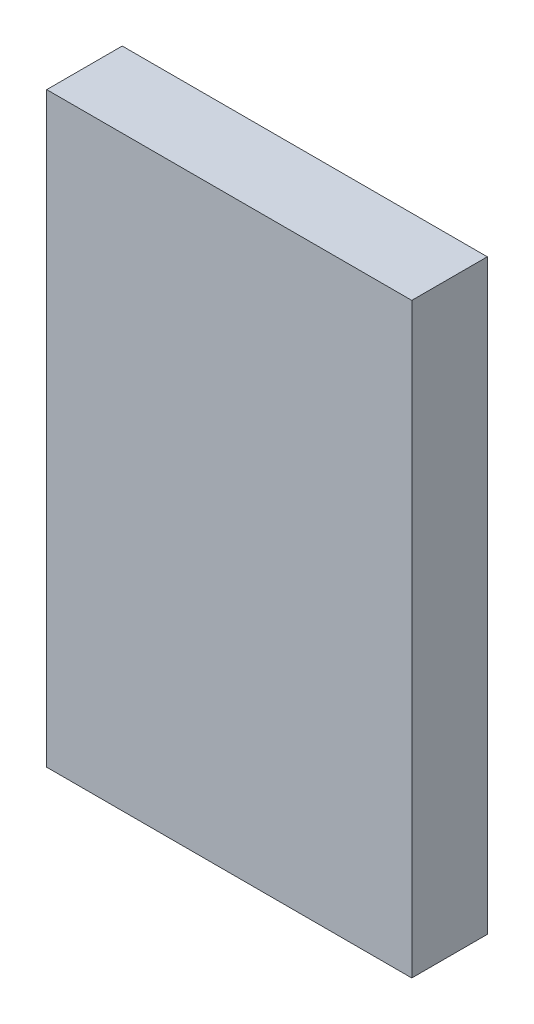
SolidWorks part; units mm, degrees
ref_plane "Front Plane" through (0, 0, 0) normal (0, 0, 1) x (1, 0, 0)
ref_plane "Top Plane" through (0, 0, 0) normal (0, 1, 0) x (1, 0, 0)
ref_plane "Right Plane" through (0, 0, 0) normal (1, 0, 0) x (0, 0, -1)
sketch "Sketch1" plane through (0, 0, 0) normal (0, 0, 1) x (1, 0, 0)
  line L0 (0.0436, 13.3694) -> (0.0436, -7.1259) construction
  line L1 (-7.2064, -7.1306) -> (-7.2064, 13.3694)
  line L2 (-7.2064, 13.3694) -> (7.2936, 13.3694)
  line L3 (7.2936, -6.9397) -> (7.2936, 13.3694)
  line L4 (-7.2064, -7.1306) -> (7.2936, 13.3694) construction
  line L5 (-7.2064, 13.3694) -> (7.2936, -6.9397) construction
  line L6 (-4.4564, -7.1306) -> (-4.4564, -4.1306)
  line L7 (-4.4564, -4.1306) -> (-1.4564, -4.1306)
  line L8 (-1.4564, -7.1306) -> (-1.4564, -4.1306)
  line L9 (4.5436, -4.1306) -> (1.5436, -4.1306)
  line L10 (1.5436, -7.1306) -> (1.5436, -4.1306)
  line L11 (4.5436, -7.1306) -> (4.5436, -4.1306)
  line L12 (1.5436, -7.1306) -> (4.5436, -7.1306)
  line L13 (-4.4564, -7.1306) -> (-1.4564, -7.1306)
  line L14 (-7.2064, -7.1306) -> (-7.2064, -9.9397)
  line L15 (-7.2064, -9.9397) -> (7.2936, -9.9397)
  line L16 (7.2936, -6.9397) -> (7.2936, -9.9397)
  point P0 (0.0775, 3.1674)
  dimension "D1" = 20.5
  dimension "D2" = 3
  dimension "D3" = 3
  dimension "D4" = 1.5
  dimension "D5" = 3
  dimension "D6" = 3
  dimension "D7" = 14.5
extrude "Boss-Extrude1" add sketch "Sketch1" along normal blind 3 contours L2 L3 L16 L15 L14 L1
